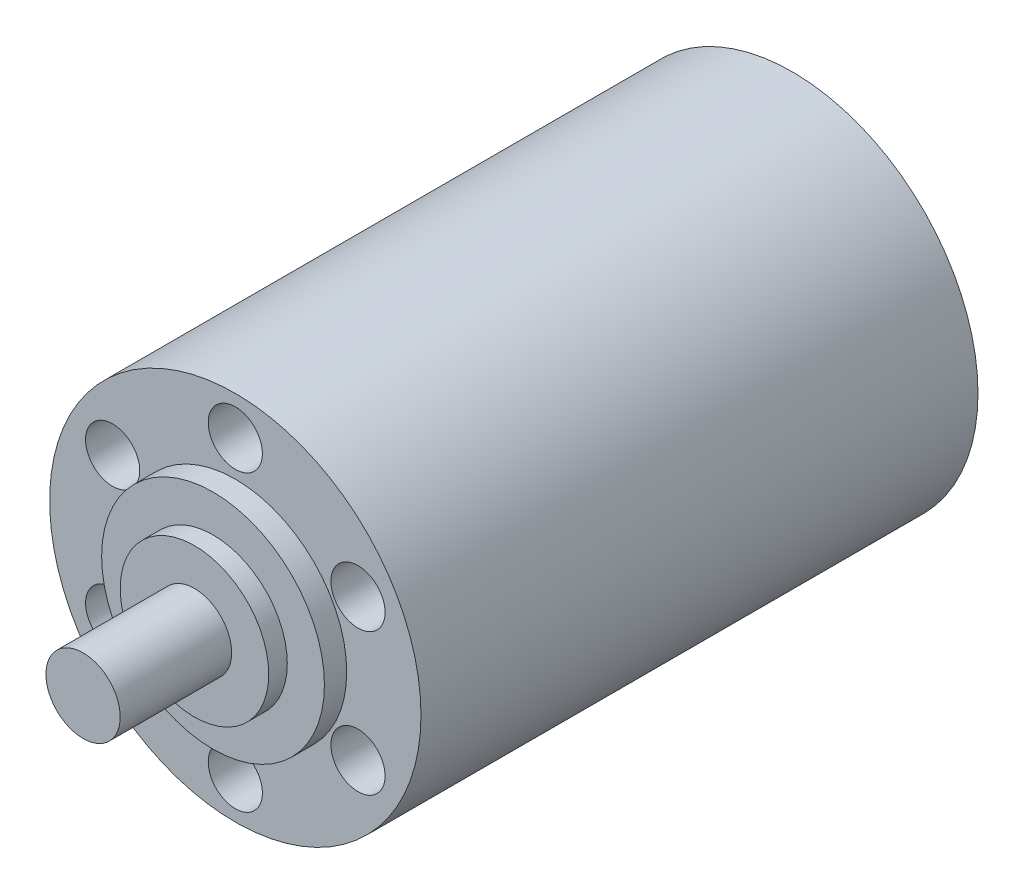
SolidWorks part; units mm, degrees
ref_plane "前视基准面" through (0, 0, 0) normal (0, 0, 1) x (1, 0, 0)
ref_plane "上视基准面" through (0, 0, 0) normal (0, 1, 0) x (1, 0, 0)
ref_plane "右视基准面" through (0, 0, 0) normal (1, 0, 0) x (0, 0, -1)
sketch "草图4" plane through (0, 0, 0) normal (0, 0, 1) x (1, 0, 0)
  circle A0 centre (0, 0) radius 50
  dimension "D1" = 100
extrude "凸台-拉伸1" add sketch "草图4" along normal blind 150
sketch "草图5" plane through (0, 0, 150) normal (0, 0, 1) x (1, 0, 0)
  circle A0 centre (0, 0) radius 30
  dimension "D1" = 60
extrude "凸台-拉伸2" add sketch "草图5" along normal blind 6
sketch "草图6" plane through (0, 0, 156) normal (0, 0, 1) x (1, 0, 0)
  circle A0 centre (0, 0) radius 20
extrude "凸台-拉伸3" add sketch "草图6" along normal blind 5
sketch "草图7" plane through (0, 0, 161) normal (0, 0, 1) x (1, 0, 0)
  circle A0 centre (0, 0) radius 10
extrude "凸台-拉伸4" add sketch "草图7" along normal blind 30
sketch "草图8" plane through (0, 0, 150) normal (0, 0, 1) x (1, 0, 0)
  line L0 (0, 0) -> (0, 50) construction
  line L1 (0, 0) -> (33.0373, 19.0741) construction
  line L2 (0, 0) -> (64.1004, 0) construction
  circle A0 centre (0, 0) radius 50 construction
  circle A1 centre (0, 39.5741) radius 7.293
  circle A2 centre (33.0373, 19.0741) radius 7.293
  circle A4 centre (0, -39.5741) radius 7.293
  circle A5 centre (-33.0373, 19.0741) radius 7.293
  circle A6 centre (33.0373, -19.0741) radius 7.293
  circle A7 centre (-33.0373, -19.0741) radius 7.293
  dimension "D3" = 60
  dimension "D1" = 2
extrude "切除-拉伸1" cut sketch "草图8" against normal blind 20
